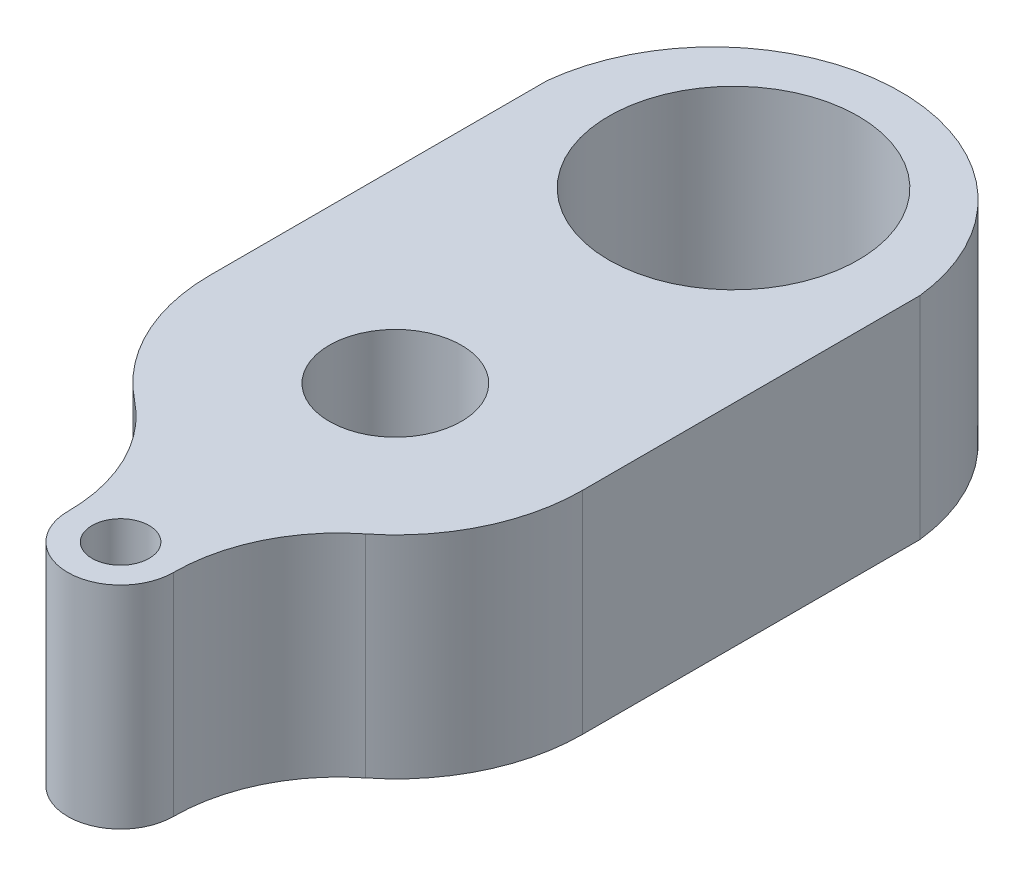
SolidWorks part; units mm, degrees
ref_plane "Front" through (0, 0, 0) normal (0, 0, 1) x (1, 0, 0)
ref_plane "Top" through (0, 0, 0) normal (0, 1, 0) x (1, 0, 0)
ref_plane "Right" through (0, 0, 0) normal (1, 0, 0) x (0, 0, -1)
sketch "Sketch1" plane through (0, 0, 0) normal (0, 1, 0) x (1, 0, 0)
  line B0 (-1.1192, 0.1226) -> (-1.1192, -1.9043)
  line B1 (0, 0.1226) -> (0, -4.3459) construction
  line B2 (0, -3.5604) -> (0.3175, -3.5604) construction
  line B3 (0, -3.8144) -> (0, 0.1226) construction
  line B4 (1.1192, 0.1226) -> (1.1192, -1.9043)
  line B5 (0.3175, -3.5604) -> (-0.3175, -3.5604) construction
  arc B6 (1.1192, -1.9043) -> (0.6942, -2.7822) centre (0, -1.9043) cw
  arc B7 (0.6942, -2.7822) -> (0.3175, -3.5604) centre (1.3097, -3.5604) ccw
  arc B8 (1.1192, 0.1226) -> (-1.1192, 0.1226) centre (0, 0) ccw
  circle B9 centre (0, -3.5604) radius 0.1714
  circle B10 centre (0, -3.5604) radius 0.3175
  arc B11 (-1.1192, -1.9043) -> (-0.6942, -2.7822) centre (0, -1.9043) ccw
  circle B12 centre (0, 0.1226) radius 0.7493
  arc B13 (-0.6942, -2.7822) -> (-0.3175, -3.5604) centre (-1.3097, -3.5604) cw
  circle B14 centre (0, -1.9094) radius 0.3969
sketch_block_instance "BLACK drive shuttle block-1"
sketch_block "BLACK drive shuttle block" parameters "D3"=0.9922, "D4"=0.3429, "D5"=0.635, "D8"=1.4986, "D9"=1.7391, "D7"=1.4986, "D2"=0.254, "D6"=2.2384, "D10"=1.2966, "D11"=0.2611, "D1"=180
extrude "Boss-Extrude1" add sketch "Sketch1" along normal blind 1.27 contours B11 B13 B10 B7 B6 B4 B8 B0 B14 B12 | B10 B9
